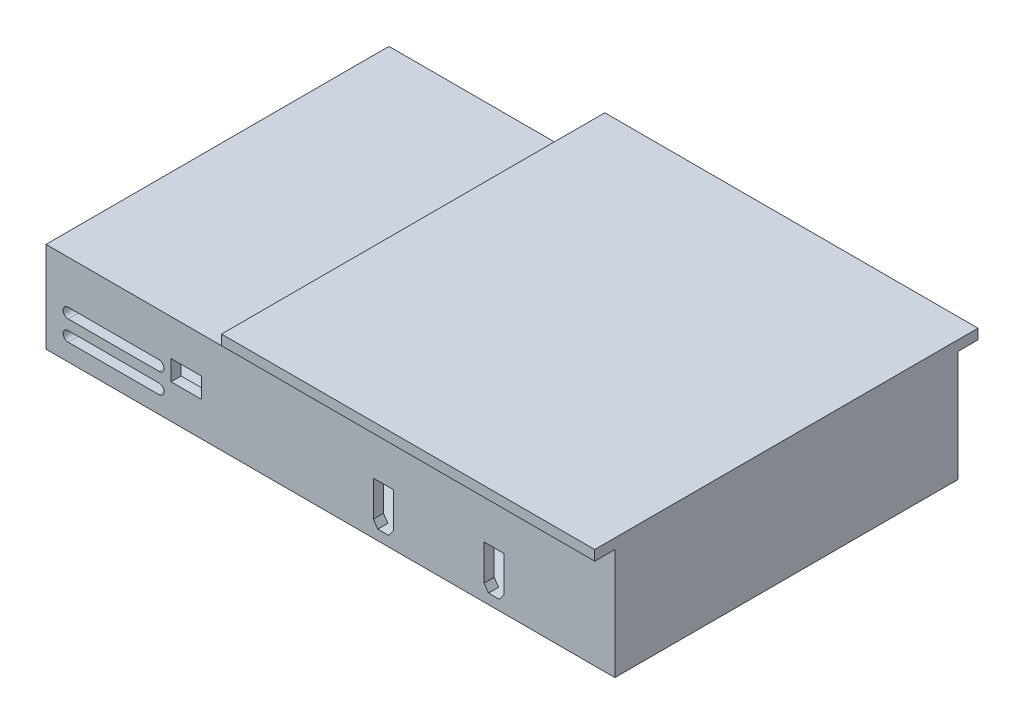
SolidWorks part; units mm, degrees
material "ABS"
ref_plane "Front Plane" through (0, 0, 0) normal (0, 0, 1) x (1, 0, 0)
ref_plane "Top Plane" through (0, 0, 0) normal (0, 1, 0) x (1, 0, 0)
ref_plane "Right Plane" through (0, 0, 0) normal (1, 0, 0) x (0, 0, -1)
sketch "Sketch1" plane through (0, 0, 0) normal (0, 1, 0) x (1, 0, 0)
  line L1 (0, 0) -> (282, 0)
  line L2 (0, 0) -> (0, 170)
  line L3 (0, 170) -> (282, 170)
  line L4 (282, 0) -> (282, 170)
  dimension "D1" = 170
  dimension "D2" = 282
extrude "Boss-Extrude1" add sketch "Sketch1" along normal blind 60
sketch "Sketch7" plane through (0, 0, 0) normal (0, -1, 0) x (1, 0, 0)
  line L0 (0, -170) -> (0, 0) construction
  line L3 (11, -37.5) -> (11, -132.5) construction
  line L4 (13.5, -37.5) -> (13.5, -132.5)
  line L5 (8.5, -37.5) -> (8.5, -132.5)
  line L6 (56, -37.5) -> (56, -132.5) construction
  line L7 (58.5, -37.5) -> (58.5, -132.5)
  line L8 (53.5, -37.5) -> (53.5, -132.5)
  line L9 (26, -37.5) -> (26, -132.5) construction
  line L10 (28.5, -37.5) -> (28.5, -132.5)
  line L11 (23.5, -37.5) -> (23.5, -132.5)
  line L12 (41, -37.5) -> (41, -132.5) construction
  line L13 (43.5, -37.5) -> (43.5, -132.5)
  line L14 (38.5, -37.5) -> (38.5, -132.5)
  line L15 (0, -85) -> (282, -85) construction
  line L16 (282, 0) -> (282, -170) construction
  arc A2 (13.5, -37.5) -> (8.5, -37.5) centre (11, -37.5) ccw
  arc A3 (8.5, -132.5) -> (13.5, -132.5) centre (11, -132.5) ccw
  arc A4 (58.5, -37.5) -> (53.5, -37.5) centre (56, -37.5) ccw
  arc A5 (53.5, -132.5) -> (58.5, -132.5) centre (56, -132.5) ccw
  arc A6 (28.5, -37.5) -> (23.5, -37.5) centre (26, -37.5) ccw
  arc A7 (23.5, -132.5) -> (28.5, -132.5) centre (26, -132.5) ccw
  arc A8 (43.5, -37.5) -> (38.5, -37.5) centre (41, -37.5) ccw
  arc A9 (38.5, -132.5) -> (43.5, -132.5) centre (41, -132.5) ccw
  point P9 (11, -85)
  point P16 (56, -85)
  point P23 (26, -85)
  point P30 (41, -85)
  point P35 (11, -35)
  point P36 (11, -135)
  point P42 (26, -35)
  point P43 (26, -135)
  point P44 (41, -35)
  point P45 (41, -135)
  point P46 (56, -35)
  point P47 (56, -135)
  dimension "D1" = 8.5
  dimension "D6" = 100
  dimension "D7" = 100
  dimension "D9" = 100
  dimension "D2" = 5
  dimension "D3" = 5
  dimension "D4" = 5
  dimension "D5" = 5
  dimension "D8" = 100
  dimension "D10" = 15
  dimension "D11" = 15
  dimension "D12" = 15
extrude "Cut-Extrude4" cut sketch "Sketch7" against normal blind 5
sketch "Sketch8" plane through (282, 0, 0) normal (1, 0, 0) x (0, 0, -1)
  line L0 (0, 60) -> (0, 0) construction
  line L1 (5, 55) -> (165, 55)
  line L2 (5, 55) -> (5, 5)
  line L3 (5, 5) -> (165, 5)
  line L4 (165, 55) -> (165, 5)
  line L5 (170, 60) -> (170, 0) construction
  line L6 (0, 0) -> (170, 0) construction
  line L7 (0, 60) -> (170, 60) construction
  dimension "D1" = 5
  dimension "D2" = 5
  dimension "D3" = 5
  dimension "D4" = 5
extrude "Cut-Extrude5" cut sketch "Sketch8" against normal blind 279
sketch "Sketch9" plane through (0, 0, 0) normal (0, 0, 1) x (1, 0, 0)
  line L0 (217.15, 25.8) -> (227.05, 25.8)
  line L1 (162.25, 25.8) -> (172.15, 25.8)
  line L2 (162.25, 25.8) -> (162.25, 8.15)
  line L3 (164.5, 5) -> (169.9, 5)
  line L4 (172.15, 25.8) -> (172.15, 8.15)
  line L5 (217.15, 25.8) -> (217.15, 8.15)
  line L6 (219.4, 5) -> (224.8, 5)
  line L7 (227.05, 25.8) -> (227.05, 8.15)
  line L8 (282, 60) -> (282, 0) construction
  line L9 (0, 0) -> (282, 0) construction
  line L10 (162.25, 8.15) -> (164.5, 5)
  line L11 (169.9, 5) -> (172.15, 8.15)
  line L12 (217.15, 8.15) -> (219.4, 5)
  line L13 (227.05, 8.15) -> (224.8, 5)
  dimension "D1" = 9.9
  dimension "D2" = 3.15
  dimension "D3" = 54.95
  dimension "D4" = 45
  dimension "D5" = 9.9
  dimension "D6" = 20.8
  dimension "D7" = 5
  dimension "D8" = 2.25
  dimension "D9" = 20.8
  dimension "D10" = 2.25
  dimension "D11" = 3.15
  dimension "D12" = 3.15
  dimension "D13" = 3.15
  dimension "D14" = 2.25
  dimension "D15" = 2.25
  dimension "D16" = 25.8
extrude "Cut-Extrude6" cut sketch "Sketch9" against normal blind 5
sketch "Sketch10" plane through (0, 0, 0) normal (-1, 0, 0) x (0, 0, 1)
  line L0 (-170, 20) -> (0, 20) construction
  line L1 (-170, 60) -> (-170, 0) construction
  line L2 (0, 60) -> (0, 0) construction
  line L3 (-170, 0) -> (0, 0) construction
  circle A0 centre (-129.2022, 20) radius 5
  circle A1 centre (-114.2022, 20) radius 5
  circle A2 centre (-99.2022, 20) radius 5
  circle A3 centre (-43.3901, 20) radius 5
  circle A4 centre (-58.3901, 20) radius 5
  circle A5 centre (-73.3901, 20) radius 5
  dimension "D1" = 15
  dimension "D3" = 10
  dimension "D4" = 10
  dimension "D5" = 10
  dimension "D6" = 10
  dimension "D7" = 10
  dimension "D8" = 10
  dimension "D2" = 15
  dimension "D9" = 15
  dimension "D10" = 15
  dimension "D11" = 20
extrude "Cut-Extrude7" cut sketch "Sketch10" against normal blind 5
sketch "Sketch11" plane through (0, 0, 0) normal (0, 0, 1) x (1, 0, 0)
  line L0 (11, 11) -> (56, 11) construction
  line L1 (11, 13.5) -> (56, 13.5)
  line L2 (11, 8.5) -> (56, 8.5)
  line L3 (11, 21) -> (56, 21) construction
  line L4 (11, 23.5) -> (56, 23.5)
  line L5 (11, 18.5) -> (56, 18.5)
  line L9 (0, 60) -> (0, 0) construction
  line L10 (0, 0) -> (282, 0) construction
  arc A0 (11, 13.5) -> (11, 8.5) centre (11, 11) ccw
  arc A1 (56, 8.5) -> (56, 13.5) centre (56, 11) ccw
  arc A2 (11, 23.5) -> (11, 18.5) centre (11, 21) ccw
  arc A3 (56, 18.5) -> (56, 23.5) centre (56, 21) ccw
  point P2 (33.5, 11)
  point P9 (33.5, 21)
  point P21 (8.5, 11)
  point P24 (33.5, 8.5)
  point P27 (58.5, 11)
  point P28 (58.5, 21)
  point P29 (8.5, 21)
  dimension "D1" = 8.5
  dimension "D2" = 8.5
  dimension "D3" = 5
  dimension "D4" = 5
  dimension "D6" = 50
  dimension "D7" = 50
  dimension "D9" = 5
sketch "Sketch12" plane through (0, 0, -170) normal (0, 0, -1) x (-1, 0, 0)
  line L0 (-56, 11) -> (-11, 11) construction
  line L1 (-56, 13.5) -> (-11, 13.5)
  line L2 (-56, 8.5) -> (-11, 8.5)
  line L3 (-56, 21) -> (-11, 21) construction
  line L4 (-56, 23.5) -> (-11, 23.5)
  line L5 (-56, 18.5) -> (-11, 18.5)
  line L9 (-282, 0) -> (0, 0) construction
  line L10 (0, 60) -> (0, 0) construction
  arc A0 (-56, 13.5) -> (-56, 8.5) centre (-56, 11) ccw
  arc A1 (-11, 8.5) -> (-11, 13.5) centre (-11, 11) ccw
  arc A2 (-56, 23.5) -> (-56, 18.5) centre (-56, 21) ccw
  arc A3 (-11, 18.5) -> (-11, 23.5) centre (-11, 21) ccw
  point P2 (-33.5, 11)
  point P12 (-33.5, 21)
  point P26 (-8.5, 11)
  point P27 (-58.5, 11)
  point P28 (-8.5, 21)
  point P29 (-58.5, 21)
  dimension "D1" = 8.5
  dimension "D2" = 5
  dimension "D3" = 5
  dimension "D5" = 50
  dimension "D6" = 50
  dimension "D8" = 8.5
  dimension "D9" = 5
extrude "Cut-Extrude8" cut sketch "Sketch11" against normal blind 5
extrude "Cut-Extrude9" cut sketch "Sketch12" against normal blind 5
sketch "Sketch14" plane through (0, 0, 0) normal (0, 0, 1) x (1, 0, 0)
  line L0 (282, 60) -> (282, 0) construction
  line L1 (282, 60) -> (97, 60)
  line L2 (282, 60) -> (282, 55)
  line L3 (282, 55) -> (97, 55)
  line L4 (97, 60) -> (97, 55)
  line L5 (0, 60) -> (282, 60) construction
  dimension "D1" = 5
  dimension "D2" = 185
extrude "Boss-Extrude2" add sketch "Sketch14" along normal blind 10
sketch "Sketch15" plane through (0, 0, -170) normal (0, 0, -1) x (-1, 0, 0)
  line L1 (-282, 60) -> (-97, 60)
  line L2 (-282, 60) -> (-282, 55)
  line L3 (-282, 55) -> (-97, 55)
  line L4 (-97, 60) -> (-97, 55)
  dimension "D1" = 5
  dimension "D2" = 185
extrude "Boss-Extrude3" add sketch "Sketch15" along normal blind 10
sketch "Sketch16" plane through (0, 0, 0) normal (0, 0, 1) x (1, 0, 0)
  line L0 (97, 60) -> (97, 55) construction
  line L1 (0, 60) -> (97, 60)
  line L2 (0, 60) -> (0, 45)
  line L3 (0, 45) -> (97, 45)
  line L4 (97, 60) -> (97, 45)
  dimension "D2" = 15
extrude "Cut-Extrude10" cut sketch "Sketch16" against normal blind 170
sketch "Sketch17" plane through (0, 0, -165) normal (0, 0, 1) x (1, 0, 0)
  line L1 (3, 45) -> (97, 45)
  line L2 (3, 45) -> (3, 40)
  line L5 (97, 55) -> (282, 55) construction
  line L7 (97, 45) -> (97, 55)
  line L8 (97, 55) -> (102, 55)
  line L9 (102, 40) -> (102, 55)
  line L11 (102, 40) -> (3, 40)
  line L12 (97, 55) -> (97, 45) construction
  dimension "D1" = 5
  dimension "D2" = 5
extrude "Boss-Extrude4" add sketch "Sketch17" along normal blind 160
sketch "Sketch18" plane through (0, 0, 0) normal (0, 0, 1) x (1, 0, 0)
  line L1 (62, 27) -> (77, 27)
  line L2 (62, 27) -> (62, 17)
  line L3 (62, 17) -> (77, 17)
  line L4 (77, 27) -> (77, 17)
  line L5 (97, 45) -> (97, 55) construction
  line L8 (0, 45) -> (97, 45) construction
  dimension "D1" = 15
  dimension "D2" = 10
  dimension "D3" = 18
  dimension "D4" = 20
extrude "Cut-Extrude11" cut sketch "Sketch18" against normal through all
sketch "Sketch19" plane through (0, 0, -165) normal (0, 0, 1) x (1, 0, 0)
  line L0 (3, 5) -> (282, 5) construction
  line L1 (282, 55) -> (277, 55)
  line L2 (282, 55) -> (282, 5)
  line L3 (282, 5) -> (277, 5)
  line L4 (277, 55) -> (277, 5)
  dimension "D1" = 5
extrude "Boss-Extrude5" add sketch "Sketch19" along normal up to next
